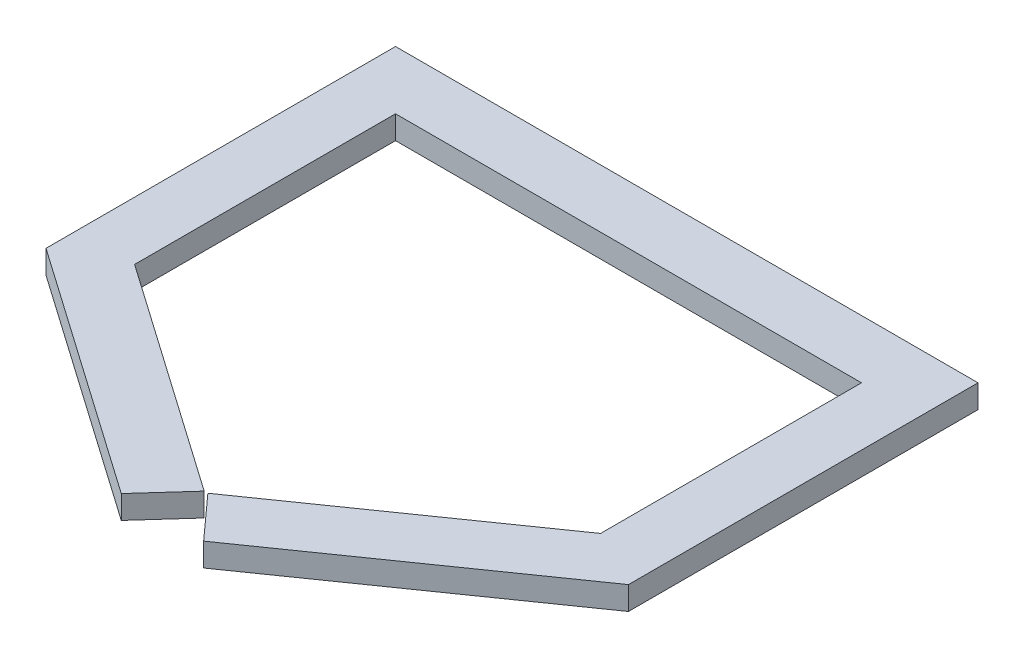
SolidWorks part; units mm, degrees
ref_plane "Front Plane" through (0, 0, 0) normal (0, 0, 1) x (1, 0, 0)
ref_plane "Top Plane" through (0, 0, 0) normal (0, 1, 0) x (1, 0, 0)
ref_plane "Right Plane" through (0, 0, 0) normal (1, 0, 0) x (0, 0, -1)
sketch "Sketch2" plane through (0, 0, 0) normal (0, 1, 0) x (1, 0, 0)
  line L1 (-24.9955, 22.5) -> (25, 22.5)
  line L2 (-24.9955, 22.5) -> (-24.9955, -7.5)
  line L4 (25, 22.5) -> (25, -7.5)
  line L5 (1.9616, -17.5) -> (20, -4.8942)
  line L6 (20, 17.5) -> (20, -4.8942)
  line L7 (-19.9955, 17.5) -> (20, 17.5)
  line L8 (-19.9955, 17.5) -> (-19.9955, -4.8945)
  line L11 (-24.9955, -7.5) -> (-3.5355, -22.5)
  line L12 (3.5355, -22.5) -> (25, -7.5)
  line L13 (-19.9955, -4.8945) -> (-1.9613, -17.5)
  line L15 (-1.9613, -17.5) -> (-0.1581, -18.7604)
  line L16 (1.9616, -17.5) -> (0.158, -18.7604)
  line L17 (-0.1581, -18.7604) -> (-3.5355, -22.5)
  line L18 (0.158, -18.7604) -> (3.5355, -22.5)
  line L19 (-3.5355, -22.5) -> (3.5355, -22.5) construction
  line L20 (-1.9613, -17.5) -> (1.9616, -17.5) construction
  point P0 (0, 0)
  dimension "D1" = 5
  dimension "D2" = 2.2
extrude "Boss-Extrude1" add sketch "Sketch2" along normal blind 2
